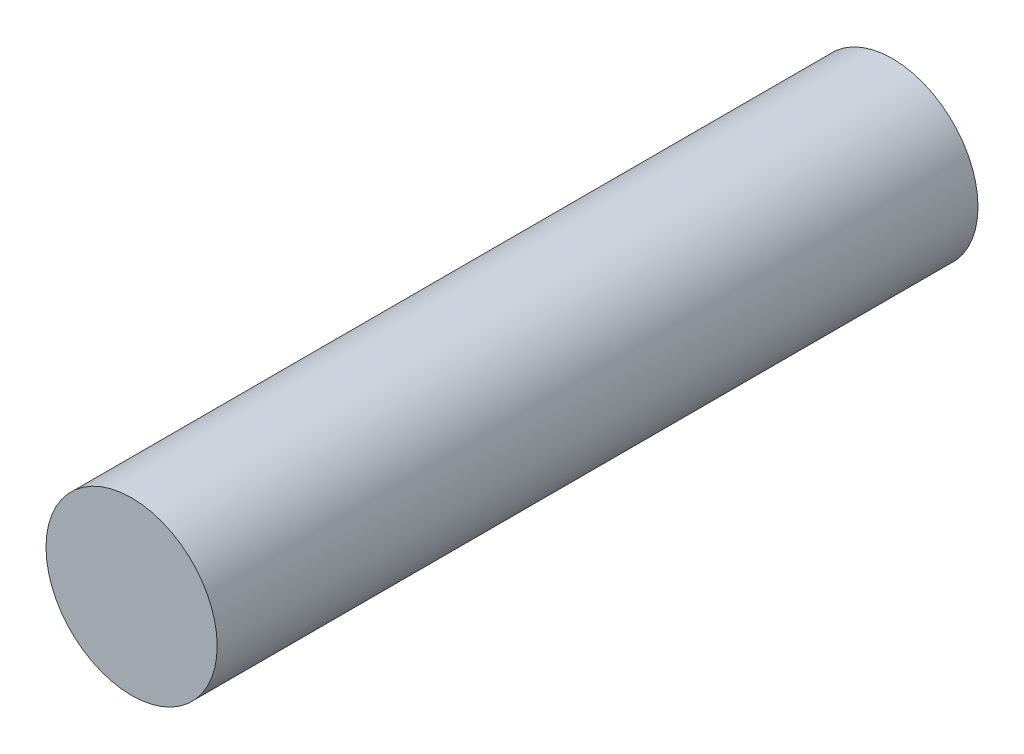
SolidWorks part; units mm, degrees
ref_plane "Front Plane" through (0, 0, 0) normal (0, 0, 1) x (1, 0, 0)
ref_plane "Top Plane" through (0, 0, 0) normal (0, 1, 0) x (1, 0, 0)
ref_plane "Right Plane" through (0, 0, 0) normal (1, 0, 0) x (0, 0, -1)
sketch "Sketch1" plane through (0, 0, 0) normal (0, 0, 1) x (1, 0, 0)
  circle A0 centre (-7.13, 4.83) radius 0.9
  dimension "D1" = 1.8
extrude "Boss-Extrude1" add sketch "Sketch1" against normal blind 8
equation "\"D1@Sketch1\"=0.18cm"
